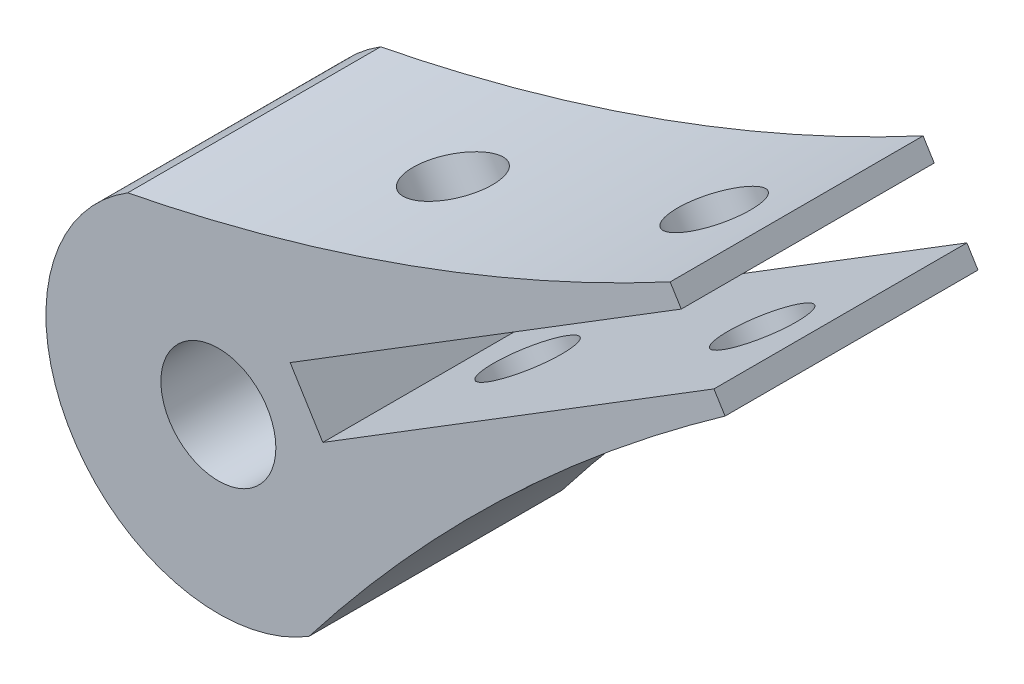
SolidWorks part; units mm, degrees
ref_plane "Front Plane" through (0, 0, 0) normal (0, 0, 1) x (1, 0, 0)
ref_plane "Top Plane" through (0, 0, 0) normal (0, 1, 0) x (1, 0, 0)
ref_plane "Right Plane" through (0, 0, 0) normal (1, 0, 0) x (0, 0, -1)
sketch "Sketch2" plane through (0, 0, 0) normal (0, 0, 1) x (1, 0, 0)
  line L0 (0, 0) -> (-9.6444, -5.9651) construction
  line L1 (19.6478, 14.8208) -> (20.1315, 14.0387)
  line L2 (20.1315, 14.0387) -> (3.122, 3.5183)
  line L3 (3.122, 3.5183) -> (4.5423, 1.2221)
  line L4 (21.5518, 11.7424) -> (4.5423, 1.2221)
  line L5 (22.0355, 10.9603) -> (21.5518, 11.7424)
  circle A0 centre (0, 0) radius 2.5
  arc A1 (-3.9452, 6.3785) -> (3.9451, -6.3786) centre (0, 0) ccw
  spline S0 degree 2 poles (-3.9452, 6.3785) (8.4943, 8.8408) (19.6478, 14.8208) knots 0 0 0 1 1 1
  spline S1 degree 2 poles (3.9451, -6.3786) (11.7037, 3.6517) (22.0355, 10.9603) knots 0 0 0 1 1 1
  point P12 (3.8322, 2.3702)
  dimension "D1" = 5
  dimension "D2" = 15
  dimension "D3" = 1.35
  dimension "D4" = 20
extrude "Boss-Extrude1" add sketch "Sketch2" along normal blind 11
ref_plane "Plane1" through (3.9451, -6.3786, 0) normal (0.526, -0.8505, 0) x (0, 0, -1)
sketch "Sketch3" plane through (3.9451, -6.3786, 0) normal (0.526, -0.8505, 0) x (0, 0, -1)
  line L0 (-11, 4.5059) -> (0, 4.5059) construction
  line L1 (-11, 4.5059) -> (0, 4.5059) construction
  circle A0 centre (-5.5, 20.5059) radius 1.75
  circle A1 centre (-5.5, 8.5059) radius 1.75
  dimension "D1" = 3.5
  dimension "D2" = 3.5
  dimension "D3" = 4
  dimension "D4" = 12
extrude "Cut-Extrude1" cut sketch "Sketch3" against normal through all
